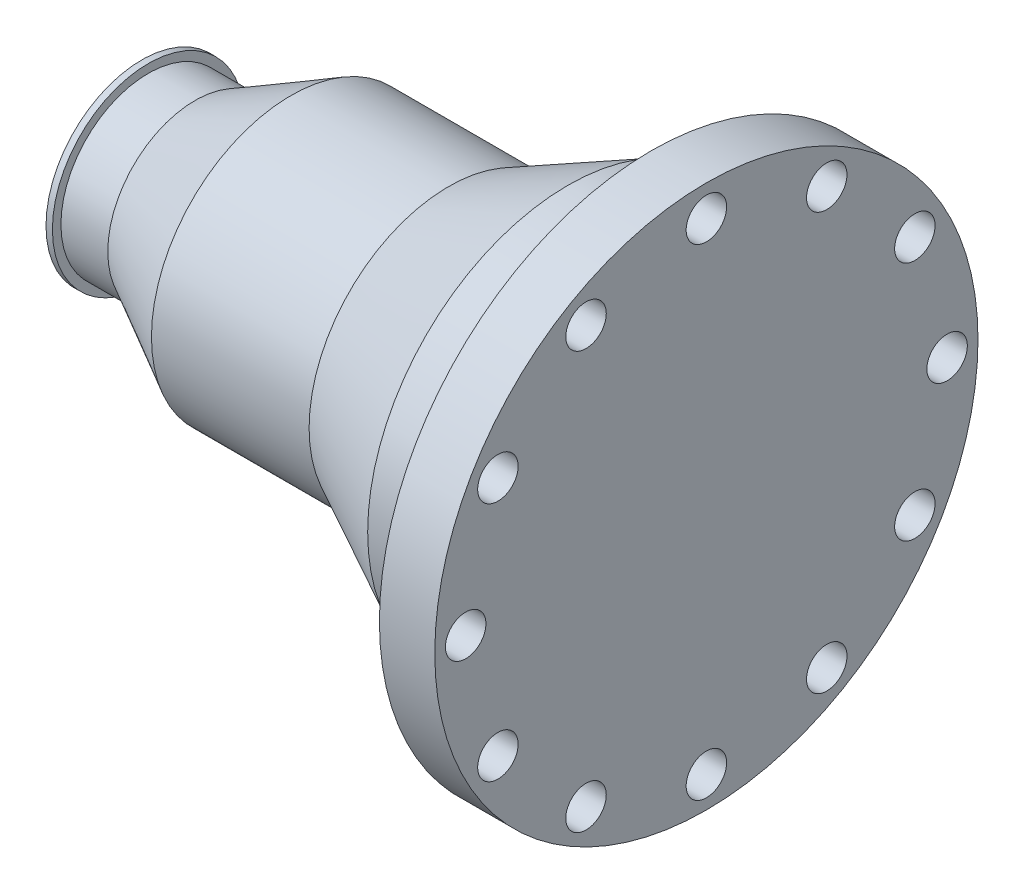
SolidWorks part; units mm, degrees
ref_plane "Спереди" through (0, 0, 0) normal (0, 0, 1) x (1, 0, 0)
ref_plane "Сверху" through (0, 0, 0) normal (0, 1, 0) x (1, 0, 0)
ref_plane "Справа" through (0, 0, 0) normal (1, 0, 0) x (0, 0, -1)
sketch "Эскиз1" plane through (0, 0, 0) normal (0, 0, 1) x (1, 0, 0)
  line L0 (0, 0) -> (265, 0)
  line L1 (0, 0) -> (0, 45)
  line L2 (0, 45) -> (3, 45)
  line L3 (3, 45) -> (3, 41)
  line L4 (3, 41) -> (25, 41)
  line L5 (25, 41) -> (70, 65.5)
  line L6 (70, 65.5) -> (144, 65.5)
  line L7 (144, 65.5) -> (200, 94)
  line L8 (200, 94) -> (220, 94)
  line L9 (220, 94) -> (220, 95)
  line L10 (220, 95) -> (239, 95)
  line L11 (239, 95) -> (239, 100)
  line L12 (239, 100) -> (239, 127.5)
  line L13 (239, 127.5) -> (265, 127.5)
  line L14 (265, 127.5) -> (265, 0)
revolve "Повернуть1" add sketch "Эскиз1" angle 360 about L0
sketch "Эскиз2" plane through (0, 0, 0) normal (0, 0, 1) x (1, 0, 0)
  line L0 (0, 0) -> (152, 0)
  line L1 (0, 0) -> (0, 31)
  line L2 (0, 45) -> (0, -45) construction
  line L3 (0, 31) -> (42, 31)
  line L4 (42, 31) -> (70, 38.5026)
  line L5 (70, 65.5) -> (70, -65.5) construction
  line L6 (90, 52.5) -> (142, 52.5)
  line L7 (143.5, 52.5) -> (146.6699, 52.5)
  line L8 (147.6699, 55) -> (152, 55)
  line L9 (152, 55) -> (152, 0)
  arc A0 (70, 38.5026) -> (90, 52.5) centre (107.8022, 5.7765) cw
  arc A1 (142, 52.5) -> (143.5, 52.5) centre (142.75, 49.8032) cw
  arc A2 (146.6699, 52.5) -> (147.6699, 55) centre (147.5934, 53.5806) cw
revolve "Вырез-Повернуть1" cut sketch "Эскиз2" angle 360 about L0
sketch "Эскиз3" plane through (0, 0, 0) normal (1, 0, 0) x (0, 0, -1)
  circle A0 centre (0, 113) radius 9.5
extrude "Вырез-Вытянуть1" cut sketch "Эскиз3" along normal through all
sketch "Эскиз4" plane through (0, 0, 0) normal (1, 0, 0) x (0, 0, -1)
  circle A0 centre (-56.5, 97.8609) radius 9.5
extrude "Вырез-Вытянуть2" cut sketch "Эскиз4" along normal through all
sketch "Эскиз5" plane through (0, 0, 0) normal (1, 0, 0) x (0, 0, -1)
  circle A0 centre (-97.8609, 56.5) radius 9.5
extrude "Вырез-Вытянуть3" cut sketch "Эскиз5" along normal through all
sketch "Эскиз6" plane through (0, 0, 0) normal (1, 0, 0) x (0, 0, -1)
  circle A0 centre (-113, 0) radius 9.5
extrude "Вырез-Вытянуть4" cut sketch "Эскиз6" along normal through all
sketch "Эскиз7" plane through (0, 0, 0) normal (1, 0, 0) x (0, 0, -1)
  circle A0 centre (-97.8609, -56.5) radius 9.5
extrude "Вырез-Вытянуть5" cut sketch "Эскиз7" along normal through all
sketch "Эскиз8" plane through (0, 0, 0) normal (1, 0, 0) x (0, 0, -1)
  circle A0 centre (-56.5, -97.8609) radius 9.5
extrude "Вырез-Вытянуть6" cut sketch "Эскиз8" along normal through all
sketch "Эскиз9" plane through (0, 0, 0) normal (1, 0, 0) x (0, 0, -1)
  circle A0 centre (0, -113) radius 9.5
extrude "Вырез-Вытянуть7" cut sketch "Эскиз9" along normal through all
sketch "Эскиз10" plane through (0, 0, 0) normal (1, 0, 0) x (0, 0, -1)
  circle A0 centre (56.5, -97.8609) radius 9.5
extrude "Вырез-Вытянуть8" cut sketch "Эскиз10" along normal through all
sketch "Эскиз11" plane through (0, 0, 0) normal (1, 0, 0) x (0, 0, -1)
  circle A0 centre (97.8609, -56.5) radius 9.5
extrude "Вырез-Вытянуть9" cut sketch "Эскиз11" along normal through all
sketch "Эскиз12" plane through (0, 0, 0) normal (1, 0, 0) x (0, 0, -1)
  circle A0 centre (113, 0) radius 9.5
extrude "Вырез-Вытянуть10" cut sketch "Эскиз12" along normal through all
sketch "Эскиз13" plane through (0, 0, 0) normal (1, 0, 0) x (0, 0, -1)
  circle A0 centre (97.8609, 56.5) radius 9.5
extrude "Вырез-Вытянуть11" cut sketch "Эскиз13" along normal through all
sketch "Эскиз14" plane through (0, 0, 0) normal (1, 0, 0) x (0, 0, -1)
  circle A0 centre (56.5, 97.8609) radius 9.5
extrude "Вырез-Вытянуть12" cut sketch "Эскиз14" along normal through all
